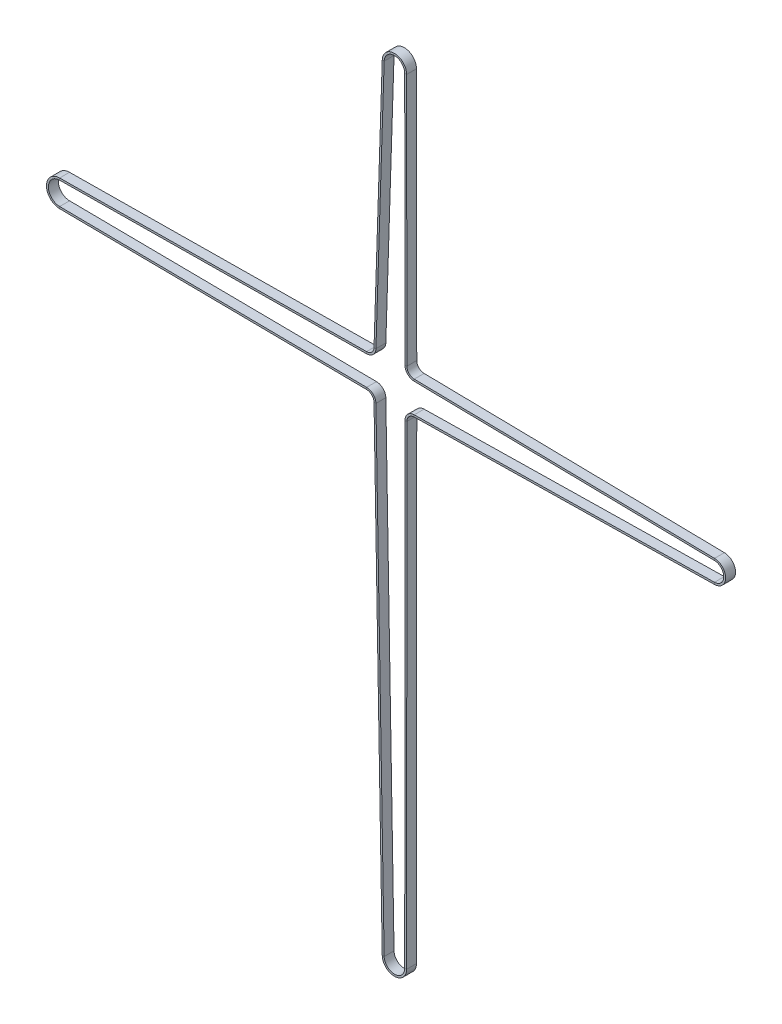
SolidWorks part; units mm, degrees
material "Silicon Rubber"
ref_plane "Front Plane" through (0, 0, 0) normal (0, 0, 1) x (1, 0, 0)
ref_plane "Top Plane" through (0, 0, 0) normal (0, 1, 0) x (1, 0, 0)
ref_plane "Right Plane" through (0, 0, 0) normal (1, 0, 0) x (0, 0, -1)
sketch "Sketch2" plane through (0, 0, 0) normal (0, 0, 1) x (1, 0, 0)
  line L0 (0, 0) -> (1, 0) construction
  line L1 (0, 0) -> (0, 1) construction
  line L2 (-6.4484, -0.1116) -> (-11.6009, 297.7348)
  line L3 (-17.44, 303.5324) -> (-209.9563, 305.491)
  line L4 (-209.9563, 319.7745) -> (-17.44, 321.733)
  line L5 (-11.6031, 327.4412) -> (-6.446, 486.2094)
  line L6 (6.4494, 486.0061) -> (6.6, 327.6271)
  line L7 (12.3997, 321.7336) -> (200.7166, 318.5319)
  line L8 (200.7166, 306.7336) -> (12.3997, 303.5319)
  line L9 (6.6, 297.6357) -> (6.4494, -0.0033)
  arc A0 (6.4494, -0.0033) -> (-6.4484, -0.1116) centre (0, 0) cw
  arc A1 (-11.6009, 297.7348) -> (-17.44, 303.5324) centre (-17.5, 297.6327) ccw
  arc A2 (-209.9563, 305.491) -> (-209.9563, 319.7745) centre (-209.8837, 312.6327) cw
  arc A3 (-17.44, 321.733) -> (-11.6031, 327.4412) centre (-17.5, 327.6327) ccw
  arc A4 (-6.446, 486.2094) -> (6.4494, 486.0061) centre (0, 486) cw
  arc A5 (6.6, 327.6271) -> (12.3997, 321.7336) centre (12.5, 327.6327) ccw
  arc A6 (200.7166, 318.5319) -> (200.7166, 306.7336) centre (200.6163, 312.6327) cw
  arc A7 (12.3997, 303.5319) -> (6.6, 297.6357) centre (12.5, 297.6327) ccw
sketch "Sketch3" plane through (0, 0, 0) normal (0, 1, 0) x (1, 0, 0)
  line L1 (6.4494, 0) -> (7.6494, 0)
  line L2 (6.4494, 0) -> (6.4494, 6.2)
  line L3 (6.4494, 6.2) -> (7.6494, 6.2)
  line L4 (7.6494, 0) -> (7.6494, 6.2)
  dimension "D1" = 1.2
  dimension "D2" = 6.2
sweep "Sweep1" add profiles "Sketch3" path "Sketch2"
